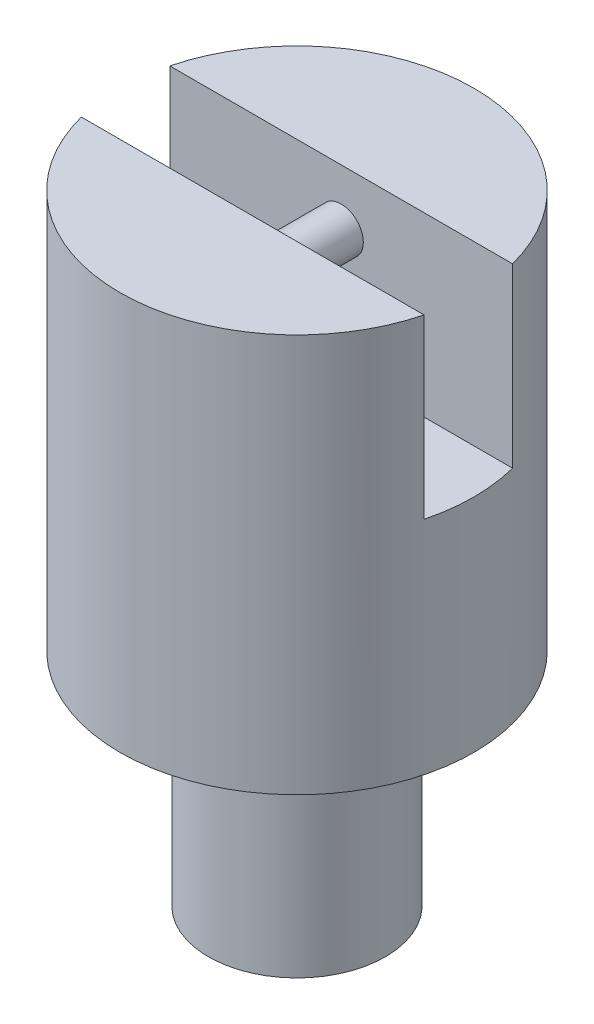
SolidWorks part; units mm, degrees
ref_plane "Front Plane" through (0, 0, 0) normal (0, 0, 1) x (1, 0, 0)
ref_plane "Top Plane" through (0, 0, 0) normal (0, 1, 0) x (1, 0, 0)
ref_plane "Right Plane" through (0, 0, 0) normal (1, 0, 0) x (0, 0, -1)
sketch "Sketch1" plane through (0, 0, 0) normal (0, 1, 0) x (1, 0, 0)
  circle A0 centre (0, 0) radius 50.8
  dimension "D1" = 101.6
extrude "Boss-Extrude1" add sketch "Sketch1" against normal blind 114.3
sketch "Sketch2" plane through (0, -114.3, 0) normal (0, -1, 0) x (-1, 0, 0)
  circle A0 centre (0, 0) radius 25.4
  dimension "D1" = 50.8
extrude "Boss-Extrude2" add sketch "Sketch2" along normal blind 63.5
sketch "Sketch3" plane through (0, 0, 0) normal (0, 1, 0) x (1, 0, 0)
  line L1 (-65.3234, -12.7) -> (65.3234, -12.7)
  line L2 (-65.3234, -12.7) -> (-65.3234, 12.7)
  line L3 (-65.3234, 12.7) -> (65.3234, 12.7)
  line L4 (65.3234, -12.7) -> (65.3234, 12.7)
  line L5 (-65.3234, -12.7) -> (65.3234, 12.7) construction
  line L6 (-65.3234, 12.7) -> (65.3234, -12.7) construction
  point P0 (0, 0)
  dimension "D1" = 25.4
extrude "Cut-Extrude5" cut sketch "Sketch3" against normal blind 50.8
sketch "Sketch5" plane through (0, 0, 12.7) normal (0, 0, -1) x (-1, 0, 0)
  line L0 (0, 55.88) -> (0, -55.88) construction
  circle A0 centre (0, -16.0759) radius 6.35
extrude "Boss-Extrude3" add sketch "Sketch5" along normal blind 50.8
